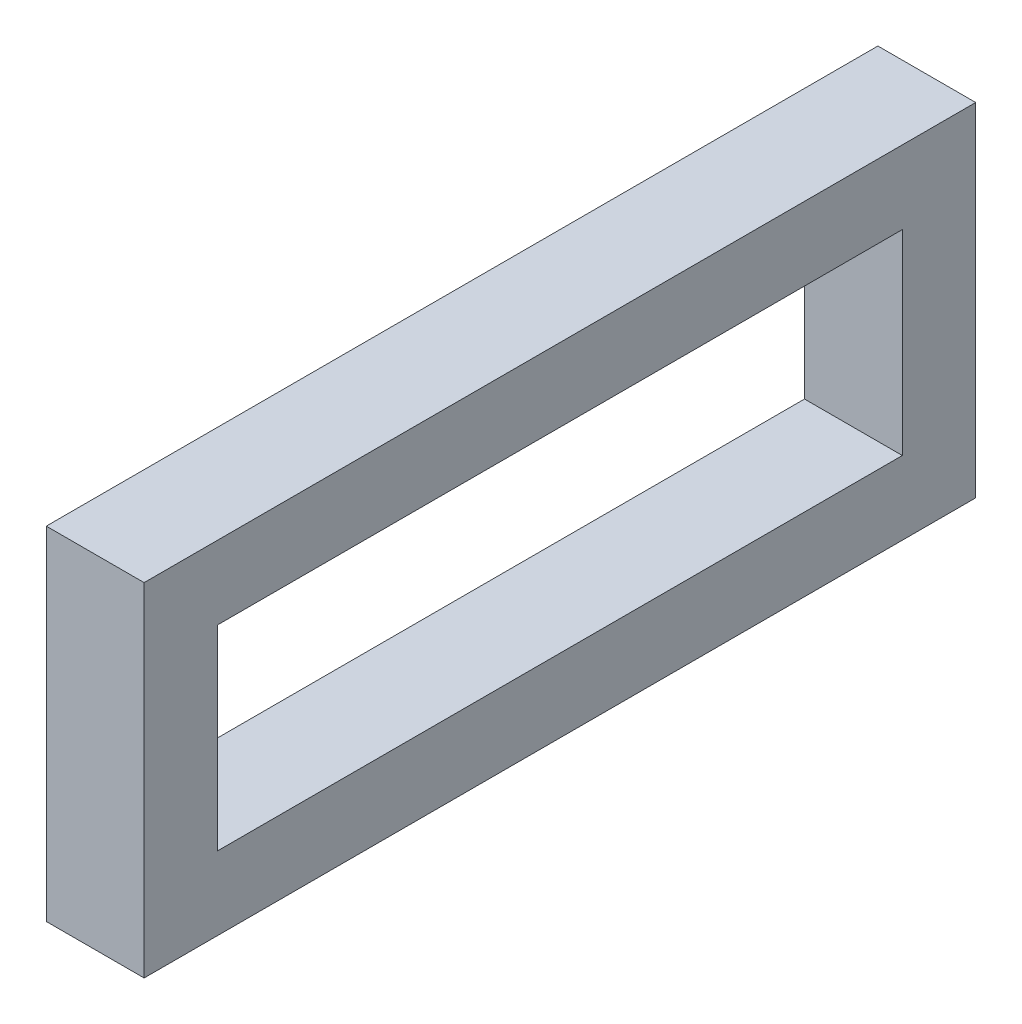
SolidWorks part; units mm, degrees
ref_plane "Front Plane" through (0, 0, 0) normal (0, 0, 1) x (1, 0, 0)
ref_plane "Top Plane" through (0, 0, 0) normal (0, 1, 0) x (1, 0, 0)
ref_plane "Right Plane" through (0, 0, 0) normal (1, 0, 0) x (0, 0, -1)
sketch "Sketch1" plane through (0, 0, 0) normal (1, 0, 0) x (0, 0, -1)
  line L1 (85, -35) -> (-85, -35)
  line L2 (85, -35) -> (85, 35)
  line L3 (85, 35) -> (-85, 35)
  line L4 (-85, -35) -> (-85, 35)
  line L5 (85, -35) -> (-85, 35) construction
  line L6 (85, 35) -> (-85, -35) construction
  line L7 (70, -20) -> (-70, -20)
  line L8 (70, -20) -> (70, 20)
  line L9 (70, 20) -> (-70, 20)
  line L10 (-70, -20) -> (-70, 20)
  line L11 (70, -20) -> (-70, 20) construction
  line L12 (70, 20) -> (-70, -20) construction
  point P0 (0, 0)
  point P6 (0, 0)
  dimension "D1" = 70
  dimension "D2" = 170
  dimension "D3" = 140
  dimension "D4" = 40
extrude "Boss-Extrude1" add sketch "Sketch1" along normal blind 20
